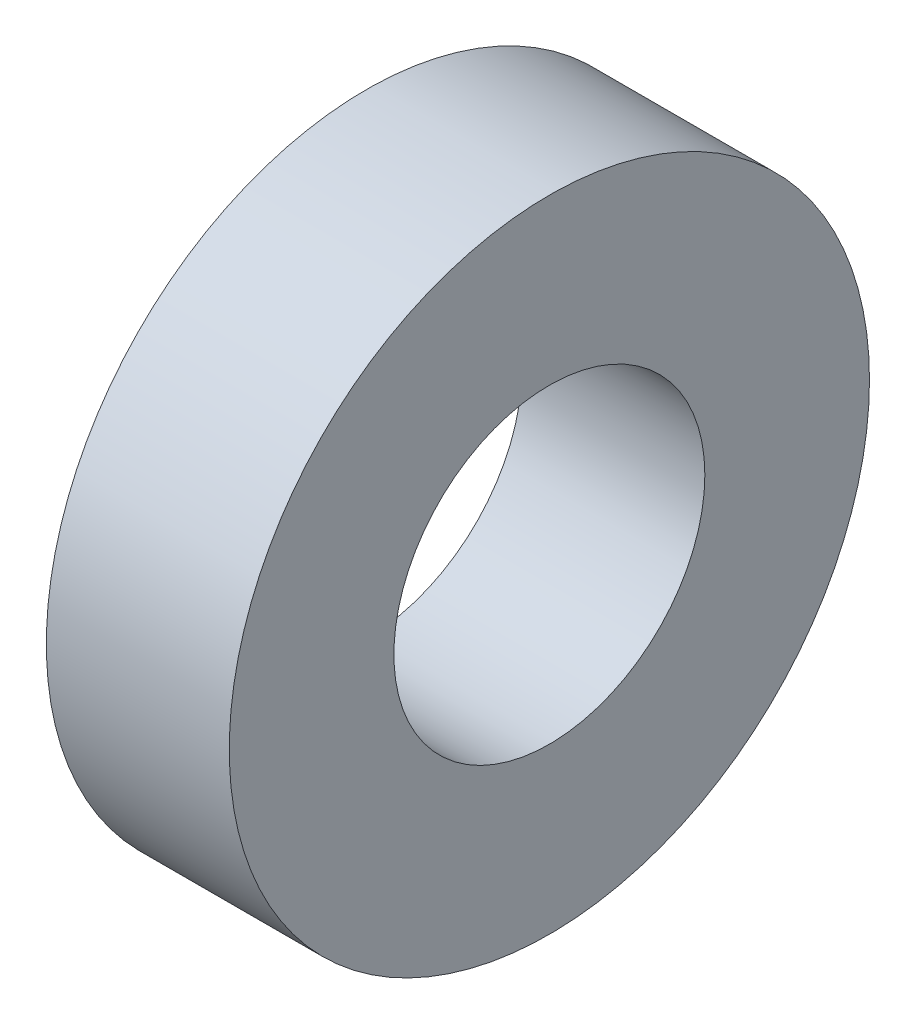
SolidWorks part; units mm, degrees
ref_plane "Front Plane" through (0, 0, 0) normal (0, 0, 1) x (1, 0, 0)
ref_plane "Top Plane" through (0, 0, 0) normal (0, 1, 0) x (1, 0, 0)
ref_plane "Right Plane" through (0, 0, 0) normal (1, 0, 0) x (0, 0, -1)
sketch "Sketch1" plane through (0, 0, 0) normal (1, 0, 0) x (0, 0, -1)
  circle A0 centre (0, 0) radius 8.5
  circle A1 centre (0, 0) radius 17.5
  dimension "D1" = 17
  dimension "D2" = 35
extrude "Boss-Extrude1" add sketch "Sketch1" along normal blind 10
